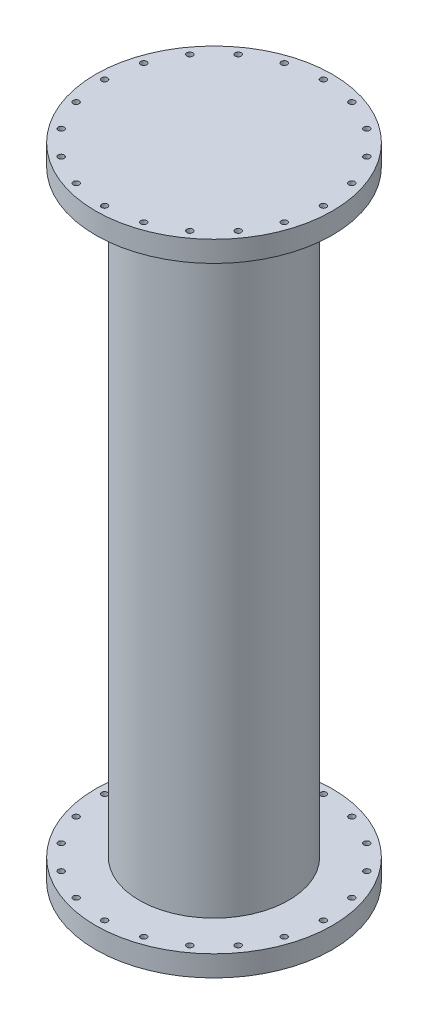
SolidWorks part; units mm, degrees
ref_plane "Plan de face" through (0, 0, 0) normal (0, 0, 1) x (1, 0, 0)
ref_plane "Plan de dessus" through (0, 0, 0) normal (0, 1, 0) x (1, 0, 0)
ref_plane "Plan de droite" through (0, 0, 0) normal (1, 0, 0) x (0, 0, -1)
sketch "Esquisse1" plane through (0, 0, 0) normal (0, 0, 1) x (1, 0, 0)
  line L0 (0, 0) -> (0, -1756.5308) construction
  line L1 (0, 0) -> (396, 0)
  line L2 (0, 0) -> (0, -70)
  line L3 (0, -70) -> (200, -70)
  line L4 (396, 0) -> (396, -70)
  line L26 (250, -70) -> (396, -70)
  line L27 (250, -2070) -> (396, -2070)
  line L29 (200, -70) -> (200, -2070)
  line L31 (250, -70) -> (250, -2070)
  line L32 (0, -2070) -> (200, -2070)
  line L33 (0, -2070) -> (0, -2140)
  line L34 (0, -2140) -> (396, -2140)
  line L35 (396, -2070) -> (396, -2140)
  dimension "D1" = 396
  dimension "D2" = 70
  dimension "D3" = 70
  dimension "D4" = 396
  dimension "D5" = 250
  dimension "D6" = 200
  dimension "D7" = 2000
revolve "Révolution1" add sketch "Esquisse1" angle 360 about L0
sketch "Esquisse2" plane through (0, 0, 0) normal (0, 1, 0) x (1, 0, 0)
  circle A0 centre (366, 0) radius 10
  dimension "D2" = 20
  dimension "D1" = 366
extrude "Enlèv. mat.-Extru.1" cut sketch "Esquisse2" against normal through all
pattern_circular "Répétition circulaire1" count 20 over 360 about axis through (0, 0, 0) along (0, 1, 0) of "Enlèv. mat.-Extru.1"
sketch "Esquisse3" plane through (0, -2140, 0) normal (0, 1, 0) x (1, 0, 0)
  circle A0 centre (0, 0) radius 255.3935
sketch "Esquisse4" plane through (0, -2140, 0) normal (0, -1, 0) x (1, 0, 0)
  circle A0 centre (0, 0) radius 255.3935
  circle A1 centre (0, 0) radius 200
  circle A2 centre (0, 230.8199) radius 10
extrude "Enlèv. mat.-Extru.2" cut sketch "Esquisse4" against normal blind 50 contours A2
pattern_circular "Répétition circulaire2" count 12 over 360 about axis through (0, 0, 0) along (0, 1, 0) of "Enlèv. mat.-Extru.2"
ref_plane "Plan1" through (0, -2070, 0) normal (0, -1, 0) x (-1, 0, 0)
split "Fractionner1" trim tools "Plan1" bodies to split 105 resulting bodies 106 107
